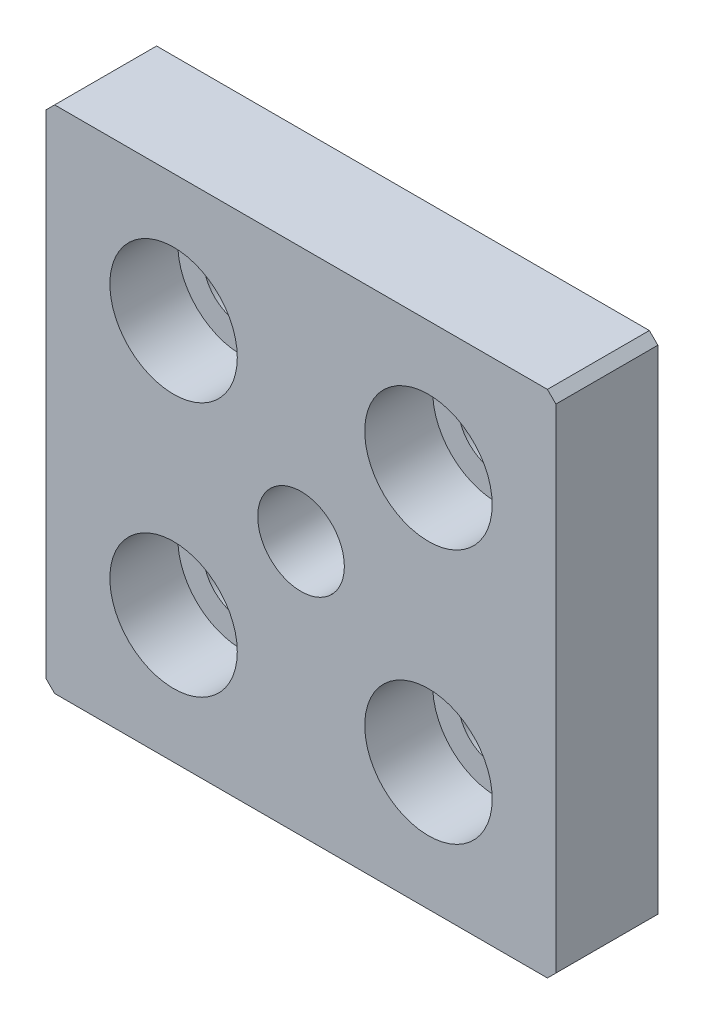
SolidWorks part; units mm, degrees
ref_plane "Front Plane" through (0, 0, 0) normal (0, 0, 1) x (1, 0, 0)
ref_plane "Top Plane" through (0, 0, 0) normal (0, 1, 0) x (1, 0, 0)
ref_plane "Right Plane" through (0, 0, 0) normal (1, 0, 0) x (0, 0, -1)
sketch "Sketch1" plane through (0, 0, 0) normal (0, 0, 1) x (1, 0, 0)
  line L1 (-30, 30) -> (30, 30)
  line L2 (-30, 30) -> (-30, -30)
  line L3 (-30, -30) -> (30, -30)
  line L4 (30, 30) -> (30, -30)
  line L5 (-30, 30) -> (30, -30) construction
  line L6 (-30, -30) -> (30, 30) construction
  point P0 (0, 0)
  dimension "D1" = 60
  dimension "D2" = 60
extrude "Boss-Extrude1" add sketch "Sketch1" along normal blind 12
hole_wizard "M12x1.75 Tapped Hole1" positions "Sketch4" profile "Sketch3" tap size "M12x1.75" standard "ANSI Metric" end condition through all
sketch "Sketch4" plane through (0, 0, 12) normal (0, 0, 1) x (1, 0, 0)
  point P0 (0, 0)
sketch "Sketch3" plane through (0, 0, 12) normal (1, 0, 0) x (0, -1, 0)
  line L0 (0, 0) -> (0, 12)
  line L1 (0, 12) -> (5.1, 12)
  line L2 (5.1, 12) -> (5.1, 0)
  line L5 (5.1, 0) -> (0, 0)
  line L11 (0, -6.35) -> (0, 107.95) construction
  dimension "Thru Tap Drill Dia." = 10.2
  dimension "Thru Tap Drill Depth" = 12
cosmetic thread "Hole Thread1" parameters "D2"=12
hole_wizard "CBORE for M8 SHCS1" positions "Sketch7" profile "Sketch6" counterbore size "M8" standard "ANSI Metric" end condition through all
sketch "Sketch7" plane through (0, 0, 12) normal (0, 0, 1) x (1, 0, 0)
  point P0 (-15, 15)
  point P2 (15, 15)
  point P4 (15, -15)
  point P6 (-15, -15)
  dimension "D1" = 30
  dimension "D2" = 30
  dimension "D3" = 15
  dimension "D4" = 15
sketch "Sketch6" plane through (-15, 15, 12) normal (1, 0, 0) x (0, -1, 0)
  line L0 (0, 0) -> (0, 12)
  line L1 (0, 12) -> (4.5, 12)
  line L3 (4.5, 12) -> (4.5, 8)
  line L4 (4.5, 8) -> (7.5, 8)
  line L5 (7.5, 8) -> (7.5, 0)
  line L7 (7.5, 0) -> (0, 0)
  line L11 (0, -6.35) -> (0, 107.95) construction
  dimension "Thru Hole Dia." = 9
  dimension "Thru Hole Depth" = 12
  dimension "C'Bore Dia." = 15
  dimension "C'Bore Depth" = 8
chamfer "Chamfer1" distance 1 angle 45 4 edges at (30, -30, 6) (-30, -30, 6) (-30, 30, 6) (30, 30, 6)
